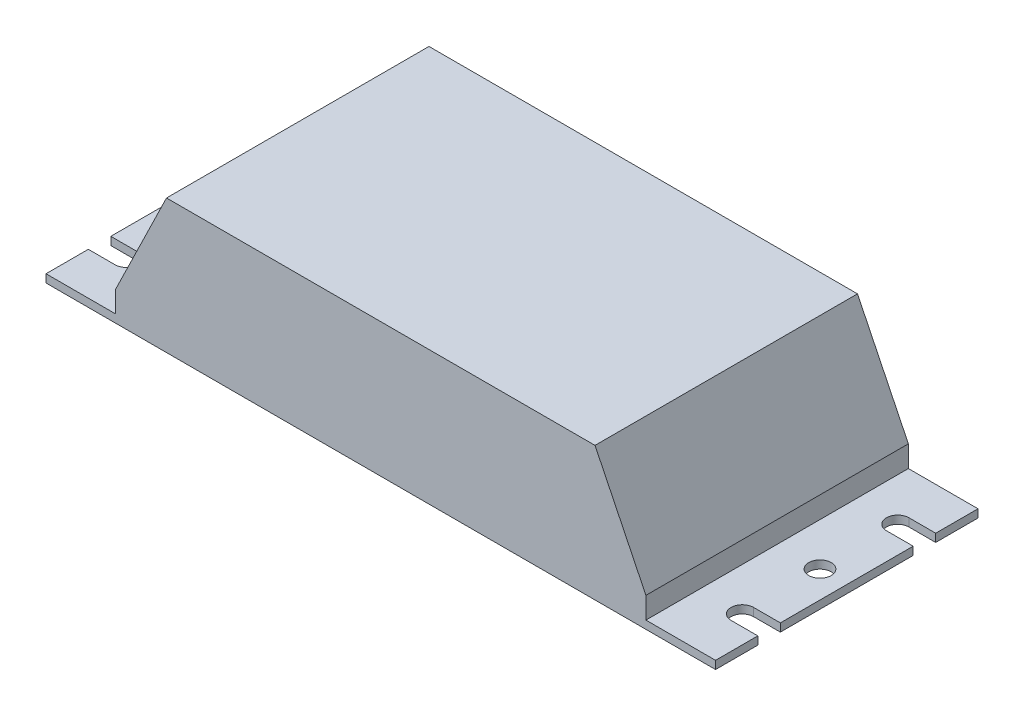
SolidWorks part; units mm, degrees
ref_plane "前视基准面" through (0, 0, 0) normal (0, 0, 1) x (1, 0, 0)
ref_plane "上视基准面" through (0, 0, 0) normal (0, 1, 0) x (1, 0, 0)
ref_plane "右视基准面" through (0, 0, 0) normal (1, 0, 0) x (0, 0, -1)
sketch "草图1" plane through (0, 0, 0) normal (0, 1, 0) x (1, 0, 0)
  line L0 (0, 68.2543) -> (0, -65.0723) construction
  line L1 (-62.5, 24.5) -> (62.5, 24.5)
  line L2 (-62.5, 24.5) -> (-62.5, -24.5)
  line L3 (-62.5, -24.5) -> (62.5, -24.5)
  line L4 (62.5, 24.5) -> (62.5, -24.5)
  line L5 (90.8467, 0) -> (-74.6184, 0) construction
  dimension "D1" = 49
  dimension "D2" = 125
extrude "凸台-拉伸1" add sketch "草图1" along normal blind 25
sketch "草图2" plane through (0, 0, 24.5) normal (0, 0, 1) x (1, 0, 0)
  line L0 (0, -13.4616) -> (0, 36.5792) construction
  line L1 (-62.5, 1.5) -> (-49.5, 1.5)
  line L2 (-62.5, 25) -> (-62.5, 0) construction
  line L3 (-49.5, 1.5) -> (-49.5, 5.5)
  line L5 (-49.5, 5.5) -> (-40, 25)
  line L6 (-62.5, 0) -> (62.5, 0) construction
  line L7 (-62.5, 25) -> (62.5, 25) construction
  line L8 (-40, 25) -> (40, 25)
  line L9 (-62.5, 1.5) -> (-62.5, 0)
  line L10 (-62.5, 0) -> (62.5, 0)
  line L11 (62.5, 1.5) -> (62.5, 0)
  line L12 (49.5, 5.5) -> (40, 25)
  line L13 (49.5, 1.5) -> (49.5, 5.5)
  line L14 (62.5, 1.5) -> (49.5, 1.5)
  point P18 (0, 0)
  point P20 (0, 25)
  dimension "D1" = 1.5
  dimension "D2" = 80
  dimension "D3" = 99
  dimension "D4" = 4
extrude "切除-拉伸1" cut sketch "草图2" against normal through all flip side to cut
sketch "草图3" plane through (0, 0, 0) normal (0, -1, 0) x (1, 0, 0)
  line L0 (-67.6208, 0) -> (73.7897, 0) construction
  line L1 (0, 38.444) -> (0, -31.9449) construction
  line L2 (-62.5, 16.6) -> (-57.5, 16.6)
  line L3 (-62.5, -24.5) -> (-62.5, 24.5) construction
  line L4 (-64.4653, 14.5) -> (-55.7705, 14.5) construction
  line L5 (-57.5, 16.6) -> (-57.5, 12.4) construction
  line L6 (-62.5, 12.4) -> (-57.5, 12.4)
  line L7 (-62.5, 16.6) -> (-62.5, 12.4)
  line L8 (57.5, 16.6) -> (57.5, 12.4) construction
  line L9 (64.4653, 14.5) -> (55.7705, 14.5) construction
  line L10 (62.5, 16.6) -> (62.5, 12.4)
  line L11 (62.5, 12.4) -> (57.5, 12.4)
  line L12 (62.5, 16.6) -> (57.5, 16.6)
  line L13 (64.4653, -14.5) -> (55.7705, -14.5) construction
  line L14 (57.5, -16.6) -> (57.5, -12.4) construction
  line L15 (-57.5, -16.6) -> (-57.5, -12.4) construction
  line L16 (-64.4653, -14.5) -> (-55.7705, -14.5) construction
  line L17 (62.5, -16.6) -> (57.5, -16.6)
  line L18 (62.5, -12.4) -> (57.5, -12.4)
  line L19 (62.5, -16.6) -> (62.5, -12.4)
  line L20 (-62.5, -16.6) -> (-62.5, -12.4)
  line L21 (-62.5, -12.4) -> (-57.5, -12.4)
  line L22 (-62.5, -16.6) -> (-57.5, -16.6)
  circle A0 centre (-57.5, 0) radius 2.1
  circle A1 centre (57.5, 0) radius 2.1
  arc A2 (-57.5, 16.6) -> (-57.5, 12.4) centre (-57.5, 14.5) cw
  arc A3 (57.5, 16.6) -> (57.5, 12.4) centre (57.5, 14.5) ccw
  arc A4 (57.5, -16.6) -> (57.5, -12.4) centre (57.5, -14.5) cw
  arc A5 (-57.5, -16.6) -> (-57.5, -12.4) centre (-57.5, -14.5) ccw
  dimension "D1" = 4.2
  dimension "D2" = 115
  dimension "D3" = 4.2
  dimension "D4" = 29
  dimension "D5" = 115
extrude "切除-拉伸2" cut sketch "草图3" against normal blind 25
